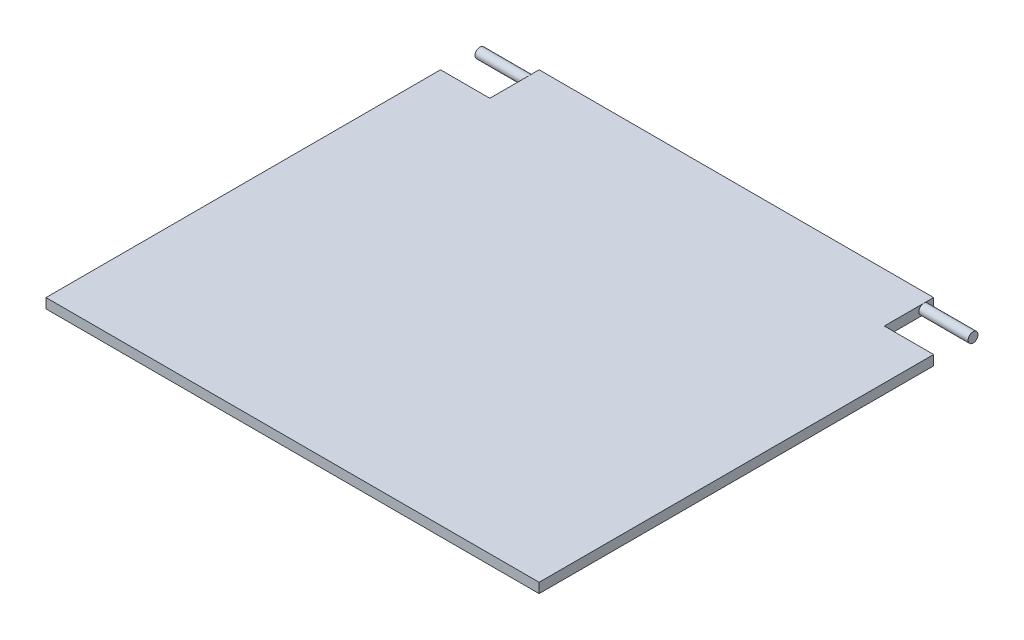
SolidWorks part; units mm, degrees
ref_plane "Front Plane" through (0, 0, 0) normal (0, 0, 1) x (1, 0, 0)
ref_plane "Top Plane" through (0, 0, 0) normal (0, 1, 0) x (1, 0, 0)
ref_plane "Right Plane" through (0, 0, 0) normal (1, 0, 0) x (0, 0, -1)
sketch "Sketch1" plane through (0, 0, 0) normal (0, 1, 0) x (1, 0, 0)
  line L1 (-250, 200) -> (250, 200)
  line L2 (-250, 200) -> (-250, -200)
  line L3 (-250, -200) -> (250, -200)
  line L4 (250, 200) -> (250, -200)
  dimension "D1" = 500
  dimension "D2" = 400
  dimension "D3" = 200
  dimension "D4" = 250
extrude "Boss-Extrude1" add sketch "Sketch1" along normal blind 10
sketch "Sketch2" plane through (0, 10, 0) normal (0, 1, 0) x (1, 0, 0)
  line L0 (250, 200) -> (-250, 200) construction
  line L1 (-200, 200) -> (200, 200)
  line L2 (-200, 200) -> (-200, 250)
  line L3 (-200, 250) -> (200, 250)
  line L4 (200, 200) -> (200, 250)
  line L5 (-250, 200) -> (-250, -200) construction
  dimension "D1" = 400
  dimension "D2" = 50
  dimension "D3" = 50
extrude "Boss-Extrude2" add sketch "Sketch2" against normal blind 10
sketch "Sketch3" plane through (-200, 0, 0) normal (-1, 0, 0) x (0, 0, 1)
  line L0 (-250, 0) -> (-250, 10) construction
  line L1 (-250, 0) -> (-200, 0) construction
  circle A0 centre (-240, 5) radius 5
  dimension "D2" = 10
  dimension "D1" = 10
  dimension "D3" = 5
extrude "Boss-Extrude5" add sketch "Sketch3" along normal blind 50
mirror "Mirror1" about plane through (0, 0, 0) normal (1, 0, 0) of "Boss-Extrude5"
